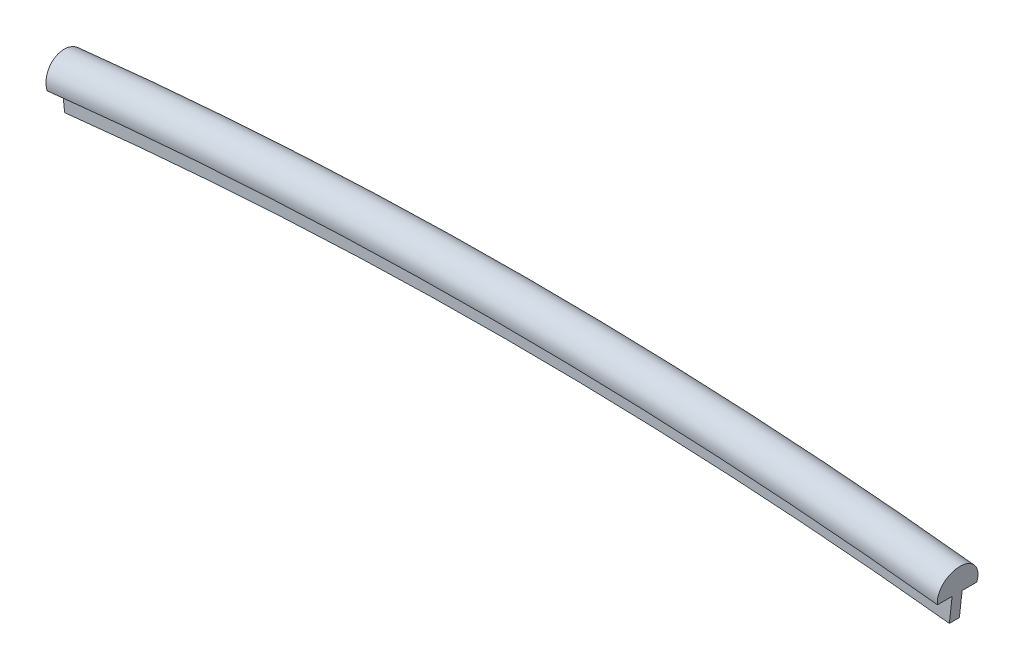
SolidWorks part; units mm, degrees
ref_plane "Front Plane" through (0, 0, 0) normal (0, 0, 1) x (1, 0, 0)
ref_plane "Top Plane" through (0, 0, 0) normal (0, 1, 0) x (1, 0, 0)
ref_plane "Right Plane" through (0, 0, 0) normal (1, 0, 0) x (0, 0, -1)
sketch "Sketch2" plane through (0, 0, 0) normal (1, 0, 0) x (0, 0, -1)
  line L0 (0, 241.3) -> (0, 0) construction
  line L2 (0, 241.3) -> (0, 239.8) construction
  line L3 (0, 239.8) -> (0.3, 239.8)
  line L4 (0, 239.8) -> (-0.3, 239.8)
  line L5 (-0.3, 239.8) -> (-0.3, 241.3)
  line L6 (0.3, 239.8) -> (0.3, 241.3)
  line L7 (0, 241.3) -> (0, 242.8) construction
  line L8 (-1.18, 241.3) -> (-0.3, 241.3)
  line L9 (0.3, 241.3) -> (1.18, 241.3)
  arc A0 (-1.18, 241.3) -> (1.18, 241.3) centre (0, 241.586) cw
  point P14 (0, 241.3)
ref_axis "Axis2" through (0, 0, 70.5976) along (0, 0, -1)
revolve "Revolve1" add sketch "Sketch2" angle 6.358 about axis through (0, 0, 70.5976) along (0, 0, -1)
